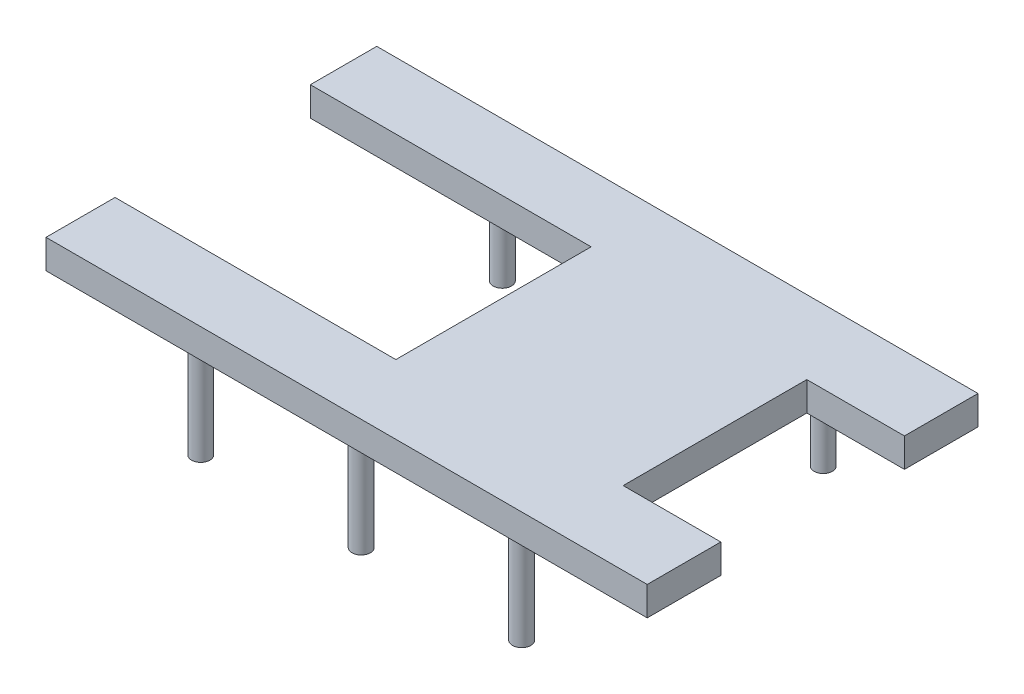
SolidWorks part; units mm, degrees
ref_plane "Front Plane" through (0, 0, 0) normal (0, 0, 1) x (1, 0, 0)
ref_plane "Top Plane" through (0, 0, 0) normal (0, 1, 0) x (1, 0, 0)
ref_plane "Right Plane" through (0, 0, 0) normal (1, 0, 0) x (0, 0, -1)
sketch "Sketch1" plane through (0, 0, 0) normal (0, 1, 0) x (1, 0, 0)
  line L1 (27.55, -13.9) -> (-27.55, -13.9)
  line L2 (27.55, -13.9) -> (27.55, 13.9)
  line L3 (27.55, 13.9) -> (-27.55, 13.9)
  line L4 (-27.55, -13.9) -> (-27.55, 13.9)
  line L5 (27.55, -13.9) -> (-27.55, 13.9) construction
  line L6 (27.55, 13.9) -> (-27.55, -13.9) construction
  point P0 (0, 0)
  dimension "D1" = 27.8
  dimension "D2" = 55.1
extrude "Boss-Extrude1" add sketch "Sketch1" along normal blind 3
sketch "Sketch2" plane through (0, 3, 0) normal (0, 1, 0) x (1, 0, 0)
  line L0 (26.7, -11.875) -> (27.55, -11.875)
  line L1 (25.525, -13.05) -> (25.525, -13.9)
  line L2 (-27.55, -13.9) -> (27.55, -13.9) construction
  line L3 (27.55, -13.9) -> (27.55, 13.9) construction
  line L4 (25.525, 13.05) -> (25.525, 13.9)
  line L5 (27.55, 13.9) -> (-27.55, 13.9) construction
  line L6 (26.7, 11.875) -> (27.55, 11.875)
  line L7 (-25.525, 13.05) -> (-25.525, 13.9)
  line L8 (-26.7, 11.875) -> (-27.55, 11.875)
  line L9 (-27.55, 13.9) -> (-27.55, -13.9) construction
  line L10 (-26.7, -11.875) -> (-27.55, -11.875)
  line L11 (-25.525, -13.05) -> (-25.525, -13.9)
  circle A0 centre (25.525, -11.875) radius 1.175
  circle A1 centre (25.525, 11.875) radius 1.175
  circle A2 centre (-25.525, 11.875) radius 1.175
  circle A3 centre (-25.525, -11.875) radius 1.175
  dimension "D1" = 2.35
  dimension "D2" = 0.85
  dimension "D4" = 2.35
  dimension "D7" = 2.35
  dimension "D10" = 2.35
  dimension "D3" = 0.85
  dimension "D5" = 0.85
  dimension "D6" = 0.85
  dimension "D8" = 0.85
  dimension "D9" = 0.85
  dimension "D11" = 0.85
  dimension "D12" = 0.85
sketch "Sketch3" plane through (0, 0, 0) normal (0, -1, 0) x (1, 0, 0)
  line L0 (-27.55, -13.9) -> (-27.55, 13.9) construction
  line L1 (-3.5, -8.25) -> (-21.15, -8.25)
  line L2 (-3.5, -8.25) -> (-3.5, 7.5)
  line L3 (-3.5, 7.5) -> (-21.15, 7.5)
  line L4 (-21.15, -8.25) -> (-21.15, 7.5)
  line L5 (-27.55, 13.9) -> (27.55, 13.9) construction
  line L6 (27.55, -13.9) -> (-27.55, -13.9) construction
  line L8 (-1.5, -10.2373) -> (-23.15, -10.2373)
  line L9 (-1.5, -10.2373) -> (-1.5, 9.9665)
  line L10 (-1.5, 9.9665) -> (-23.15, 9.9665)
  line L11 (-23.15, -10.2373) -> (-23.15, 9.9665)
  line L12 (-3.5, 7.5) -> (-21.15, 7.5)
  line L13 (-3.5, 7.5) -> (-3.5, -8.25)
  line L14 (-3.5, -8.25) -> (-21.15, -8.25)
  line L15 (-21.15, 7.5) -> (-21.15, -8.25)
  dimension "D1" = 15.75
  dimension "D2" = 17.65
  dimension "D3" = 6.4
  dimension "D4" = 6.4
  dimension "D5" = 5.65
  dimension "D6" = 2
  dimension "D7" = 20.2038
  dimension "D8" = 2
  dimension "D9" = 2.4665
extrude "Cut-Extrude1" cut sketch "Sketch3" against normal through all contours L4 L1 L2 L3 | L11 L8 L9 L10 L1 L4 L3 L2
sketch "Sketch4" plane through (0, 3, 0) normal (0, 1, 0) x (1, 0, 0)
  line L0 (-23.15, 10.2373) -> (-23.15, -9.9665)
  line L1 (-23.15, 10.2373) -> (-42.3046, 10.2373)
  line L2 (-23.15, -9.9665) -> (-42.3046, -9.9665)
  line L3 (-42.3046, 10.2373) -> (-42.3046, -9.9665)
extrude "Cut-Extrude2" cut sketch "Sketch4" against normal through all
sketch "Sketch5" plane through (0, 3, 0) normal (0, 1, 0) x (1, 0, 0)
  line L0 (27.55, 0) -> (27.55, 9.5)
  line L1 (27.55, -13.9) -> (27.55, 13.9) construction
  line L2 (27.55, 0) -> (27.55, -9.5)
  line L3 (27.55, 9.5) -> (27.55, -9.5)
  line L4 (27.55, 9.5) -> (21.55, 9.5)
  line L5 (27.55, -9.5) -> (21.55, -9.5)
  line L6 (21.55, 9.5) -> (21.55, -9.5)
  line M10 (27.55, -13.9) -> (27.55, 13.9)
  dimension "D1" = 9.5
  dimension "D2" = 9.5
  dimension "D3" = 6
extrude "Cut-Extrude3" cut sketch "Sketch5" against normal blind 10 contours L4 L6 L5 M10
sketch "Sketch7" plane through (27.55, 0, 0) normal (1, 0, 0) x (0, 0, -1)
  line L0 (9.5, 3) -> (9.5, 0)
  line L1 (9.5, 3) -> (13.9, 3)
  line L2 (9.5, 0) -> (13.9, 0)
  line L3 (13.9, 3) -> (13.9, 0)
  line L4 (13.9, 3) -> (13.9, 0) construction
  line L5 (-9.5, 3) -> (-9.5, 0)
  line L6 (-9.5, 3) -> (-13.9, 3)
  line L7 (-9.5, 0) -> (-13.9, 0)
  line L8 (-13.9, 3) -> (-13.9, 0)
  line L9 (-13.9, 3) -> (-13.9, 0) construction
  dimension "D1" = 0
  dimension "D2" = 0
extrude "Boss-Extrude2" add sketch "Sketch7" along normal blind 4.1
sketch "Sketch8" plane through (-27.55, 0, 0) normal (-1, 0, 0) x (0, 0, 1)
  line L0 (-13.9, 0) -> (-10.2373, 0)
  line L1 (-13.9, 0) -> (-13.9, 3)
  line L2 (-10.2373, 0) -> (-10.2373, 3)
  line L3 (-13.9, 3) -> (-10.2373, 3)
  line L5 (-13.9, 3) -> (-10.2373, 3) construction
  line L6 (9.9665, 0) -> (9.9665, 3)
  line L7 (9.9665, 0) -> (13.9, 0)
  line L8 (9.9665, 3) -> (13.9, 3)
  line L9 (13.9, 0) -> (13.9, 3)
  line L10 (13.9, 3) -> (13.9, 0) construction
  dimension "D1" = 0
  dimension "D2" = 0
extrude "Boss-Extrude3" add sketch "Sketch8" along normal blind 3
sketch "Sketch9" plane through (0, 0, -13.9) normal (0, 0, -1) x (-1, 0, 0)
  line L0 (-31.65, 3) -> (-31.65, 0)
  line L1 (-31.65, 3) -> (30.55, 3)
  line L2 (-31.65, 0) -> (30.55, 0)
  line L3 (30.55, 3) -> (30.55, 0)
  line L4 (30.55, 3) -> (30.55, 0) construction
  dimension "D1" = 0
extrude "Boss-Extrude4" add sketch "Sketch9" along normal blind 3.21
sketch "Sketch10" plane through (0, 0, 13.9) normal (0, 0, 1) x (1, 0, 0)
  line L0 (-30.55, 0) -> (-30.55, 3)
  line L1 (-30.55, 0) -> (31.65, 0)
  line L2 (-30.55, 3) -> (31.65, 3)
  line L3 (31.65, 0) -> (31.65, 3)
  line L4 (31.65, 3) -> (31.65, 0) construction
  dimension "D1" = 0
extrude "Boss-Extrude5" add sketch "Sketch10" along normal blind 3.21
sketch "Sketch11" plane through (0, 0, 0) normal (0, -1, 0) x (1, 0, 0)
  line L0 (-30.55, 17.11) -> (31.65, 17.11) construction
  line L1 (-30.55, 9.9665) -> (-30.55, 17.11) construction
  line L2 (31.65, -17.11) -> (-30.55, -17.11) construction
  line L3 (-30.55, -17.11) -> (-30.55, -10.2373) construction
  circle A0 centre (-16.05, 15.6) radius 0.95
  circle A1 centre (-16.05, -15.6) radius 0.95
  circle A2 centre (0.55, -15.6) radius 0.95
  circle A3 centre (0.55, 15.6) radius 0.95
  circle A4 centre (17.15, 15.6) radius 0.95
  circle A5 centre (17.15, -15.6) radius 0.95
  dimension "D1" = 1.51
  dimension "D2" = 1.9
  dimension "D4" = 1.9
  dimension "D5" = 1.51
  dimension "D6" = 14.5
  dimension "D7" = 1.9
  dimension "D8" = 31.1
  dimension "D9" = 1.51
  dimension "D10" = 1.9
  dimension "D11" = 1.51
  dimension "D12" = 31.1
  dimension "D13" = 1.9
  dimension "D14" = 47.7
  dimension "D15" = 1.51
  dimension "D16" = 1.9
  dimension "D17" = 1.51
  dimension "D18" = 47.7
  dimension "D3" = 14.5
extrude "Boss-Extrude6" add sketch "Sketch11" along normal blind 10
